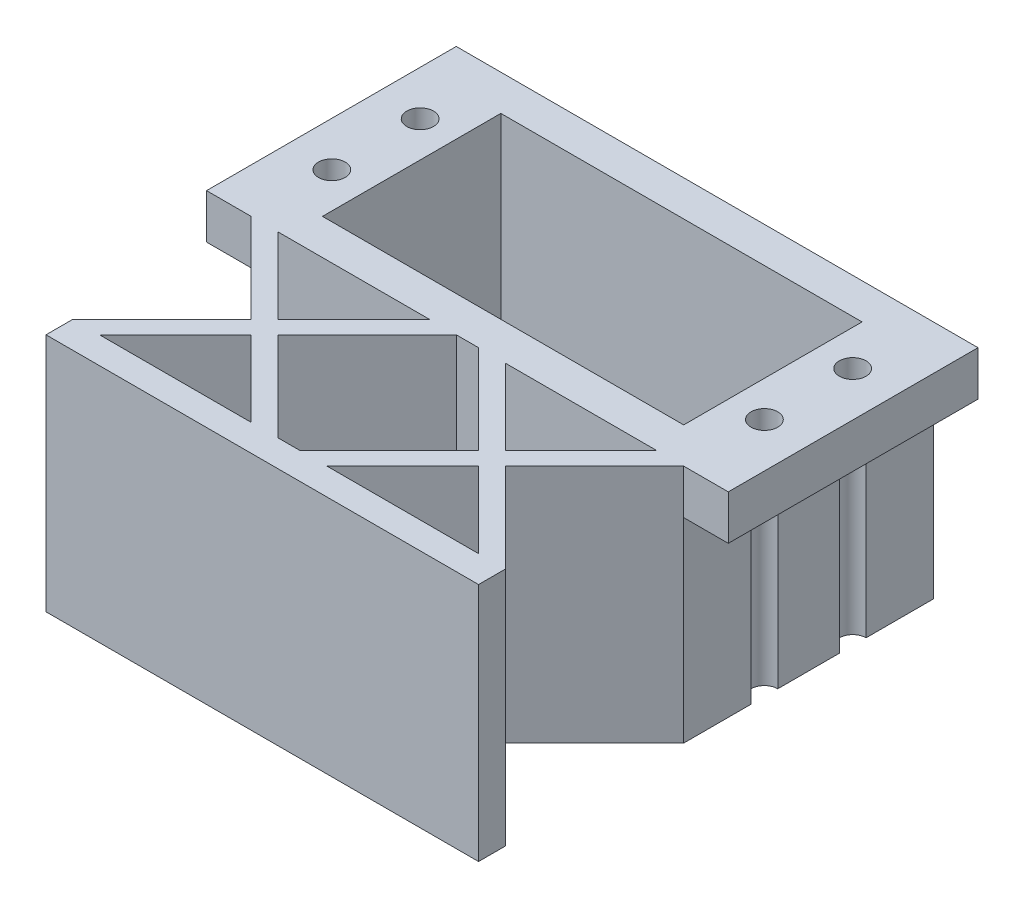
SolidWorks part; units mm, degrees
ref_plane "Front Plane" through (0, 0, 0) normal (0, 0, 1) x (1, 0, 0)
ref_plane "Top Plane" through (0, 0, 0) normal (0, 1, 0) x (1, 0, 0)
ref_plane "Right Plane" through (0, 0, 0) normal (1, 0, 0) x (0, 0, -1)
sketch "Sketch1" plane through (0, 0, 0) normal (0, 1, 0) x (1, 0, 0)
  line L0 (4, 24) -> (44.5, 24)
  line L1 (0, 0) -> (48.5, 0) construction
  line L2 (0, 0) -> (0, 28)
  line L3 (0, 28) -> (48.5, 28)
  line L4 (48.5, 0) -> (48.5, 28)
  line L5 (44.5, 4) -> (44.5, 24)
  line L6 (4, 4) -> (44.5, 4)
  line L7 (4, 4) -> (4, 24)
  line L8 (24.25, 0) -> (24.25, 28) construction
  line L9 (0, 0) -> (20, -20) construction
  line L10 (20, -20) -> (23, -20) construction
  line L11 (23, -20) -> (3, 0) construction
  line L12 (3, 0) -> (20, 0)
  line L13 (20, 0) -> (11.5, -8.5)
  line L14 (13, -10) -> (23, 0)
  line L15 (11.5, -11.5) -> (3, -20)
  line L16 (3, -20) -> (0, -20) construction
  line L17 (0, -20) -> (10, -10)
  line L18 (0, 0) -> (10, -10)
  line L19 (11.5, -11.5) -> (20, -20)
  line L20 (11.5, -8.5) -> (3, 0)
  line L21 (13, -10) -> (23, -20)
  line L22 (45.5, 0) -> (28.5, 0)
  line L23 (37, -8.5) -> (45.5, 0)
  line L24 (28.5, 0) -> (37, -8.5)
  line L25 (35.5, -10) -> (25.5, 0)
  line L26 (35.5, -10) -> (25.5, -20)
  line L27 (28.5, -20) -> (25.5, -20) construction
  line L28 (37, -11.5) -> (28.5, -20)
  line L29 (37, -11.5) -> (45.5, -20)
  line L30 (45.5, -20) -> (48.5, -20) construction
  line L31 (48.5, -20) -> (38.5, -10)
  line L32 (48.5, 0) -> (38.5, -10)
  line L33 (25.5, 0) -> (23, 0)
  line L34 (45.5, -20) -> (28.5, -20)
  line L35 (0, -20) -> (48.5, -20) construction
  line L36 (0, -20) -> (0, -23)
  line L37 (0, -23) -> (48.5, -23)
  line L38 (48.5, -20) -> (48.5, -23)
  line L39 (25.5, -20) -> (23, -20)
  line L40 (20, -20) -> (3, -20)
  dimension "D2" = 40.5
  dimension "D3" = 20
  dimension "D4" = 20
  dimension "D5" = 3
  dimension "D1" = 4
extrude "Boss-Extrude1" add sketch "Sketch1" along normal blind 26.9
sketch "Sketch2" plane through (0, 26.9, 0) normal (0, 1, 0) x (1, 0, 0)
  line L0 (48.5, 28) -> (0, 28) construction
  line L1 (0, 0) -> (-5, 0)
  line L2 (0, 0) -> (0, 28)
  line L3 (0, 28) -> (-5, 28)
  line L4 (-5, 0) -> (-5, 28)
  line L5 (24.25, 28) -> (24.25, 0) construction
  line L6 (25.5, 0) -> (23, 0) construction
  line L7 (48.5, 28) -> (53.5, 28)
  line L8 (53.5, 0) -> (53.5, 28)
  line L9 (48.5, 0) -> (53.5, 0)
  line L10 (48.5, 0) -> (48.5, 28)
  line L11 (-0.05, 28) -> (-0.05, 0) construction
  line L12 (0, 14) -> (24.25, 14) construction
  circle A0 centre (0, 18.95) radius 1.5
  circle A1 centre (0, 9.05) radius 1.5
  circle A2 centre (48.5, 9.05) radius 1.5
  circle A3 centre (48.5, 18.95) radius 1.5
  line M16 (48.5, 0) -> (48.5, 28)
  line M18 (0, 28) -> (0, 0)
  dimension "D3" = 3
  dimension "D1" = 5
  dimension "D2" = 24.3
  dimension "D4" = 9.9
extrude "Boss-Extrude2" add sketch "Sketch2" against normal blind 5 contours A1 A0 L3 L4 L1 M18 | A3 A2 L9 L8 L7 M16
sketch "Sketch3" plane through (0, 26.9, 0) normal (0, 1, 0) x (1, 0, 0)
  line L0 (0, 14) -> (24.25, 14) construction
  line L1 (0, 0) -> (0, 28) construction
  line L2 (24.25, 14) -> (24.25, 28) construction
  circle A0 centre (0, 18.95) radius 1.5
  circle A1 centre (0, 18.95) radius 1.5 construction
  circle A2 centre (0, 9.05) radius 1.5
  circle A3 centre (48.5, 9.05) radius 1.5
  circle A4 centre (48.5, 18.95) radius 1.5
extrude "Cut-Extrude1" cut sketch "Sketch3" against normal through all
